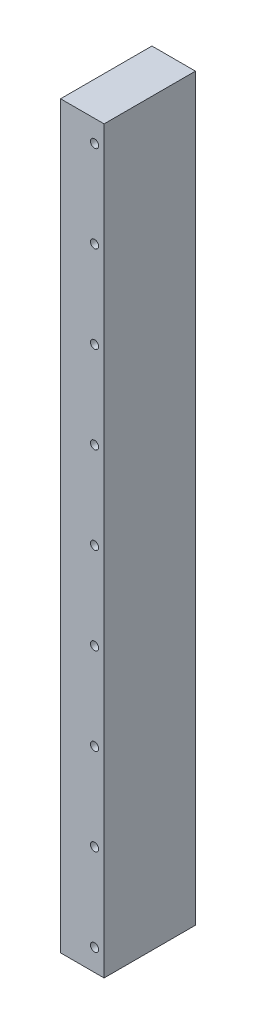
SolidWorks part; units mm, degrees
ref_plane "Top" through (0, 0, 0) normal (0, 0, 1) x (1, 0, 0)
ref_plane "Front" through (0, 0, 0) normal (0, 1, 0) x (1, 0, 0)
ref_plane "Right" through (0, 0, 0) normal (1, 0, 0) x (0, 0, -1)
sketch "Profile Sketch" plane through (0.0456, 0, -0.0242) normal (0, 1, 0) x (-1, 0, 0)
  line L1 (8.0456, 0.0242) -> (0.0456, 0.0242)
  line L2 (0.0456, 0.0242) -> (0.0456, -16.7758)
  line L3 (0.0456, -16.7758) -> (8.0456, -16.7758)
  line L5 (8.0456, -16.7758) -> (8.0456, 0.0242)
  line L12 (8.0456, 0.3949) -> (8.0456, 1.3939) construction
  line L13 (1.7956, 0.0242) -> (1.7956, 4.0449) construction
  dimension "D2" = 1.75
  dimension "Reel Width" = 8
  dimension "Height" = 16.8
extrude "Profile Extrude" add sketch "Profile Sketch" along normal blind 136
sketch "Pocket Sketch" plane through (0, 0, 0) normal (0, 1, 0) x (1, 0, 0)
  line L0 (-1.75, 0) -> (-1.75, -2.6213) construction
  line L2 (-8, 0) -> (0, 0) construction
  line L4 (-7.425, 0) -> (-3.075, 0)
  line L5 (-7.425, 0) -> (-7.425, 2.5)
  line L6 (-7.425, 2.5) -> (-3.075, 2.5)
  line L7 (-3.075, 0) -> (-3.075, 2.5)
  point P9 (-5.25, 0)
  dimension "D1" = 1.75
  dimension "Width" = 4.35
  dimension "Depth" = 2.5
  dimension "Center From Pins" = 3.5
extrude "Pocket Cut" [suppressed] cut sketch "Pocket Sketch" along normal through all
sketch "Index Hole Sketch" plane through (0, 0, 0) normal (0, 0, 1) x (1, 0, 0)
  circle A0 centre (-1.75, 4) radius 0.75
  dimension "D2" = 1.5
  dimension "D3" = 4
  dimension "D1" = 1.75
extrude "First Index Hole Cut" cut sketch "Index Hole Sketch" against normal blind 5
sketch "Index Hole Reinforcement Sketch" [suppressed] plane through (0, 0, 0) normal (0, 0, 1) x (1, 0, 0)
  line L1 (-3.2, 5.3775) -> (-3.2, 2.6225)
  line L2 (-3.2, 88) -> (-3.2, 0) construction
  arc A0 (-3.2, 5.3775) -> (-3.2, 2.6225) centre (-1.75, 4) ccw
  dimension "D1" = 2
extrude "Index Hole Reinforcement" [suppressed] add sketch "Index Hole Reinforcement Sketch" against normal up to next
pattern_linear "Index Hole Pattern" count 9 spacing 16 along (0, 1, 0) of "First Index Hole Cut", "Index Hole Reinforcement"
ref_plane "Mid Plane" through (0, 68, 0) normal (0, -1, 0) x (-1, 0, 0)
equation "\"D2@Index Hole Sketch\"=1.50mm"
